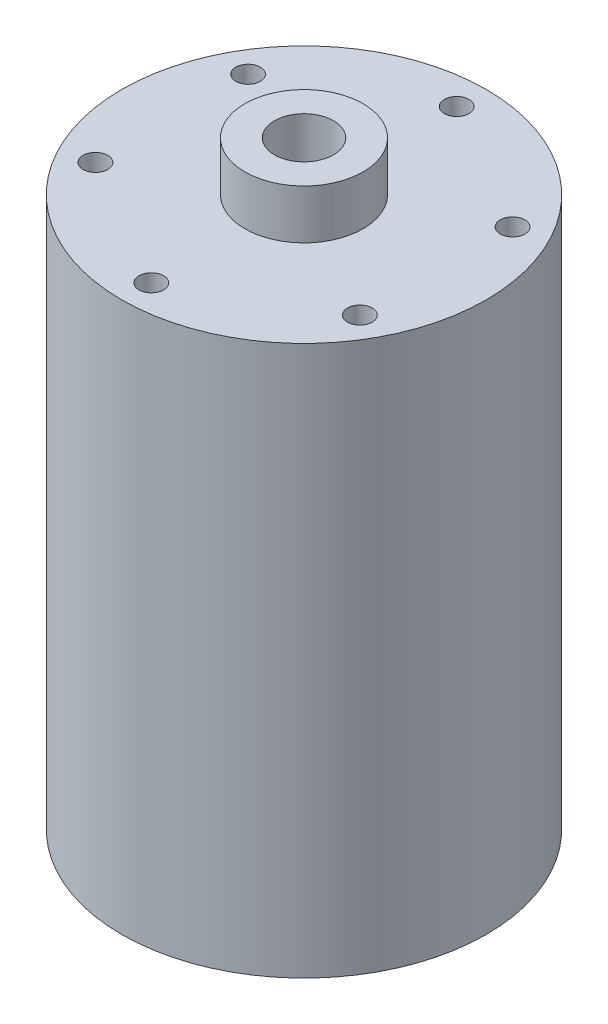
SolidWorks part; units mm, degrees
material "Plain Carbon Steel"
ref_plane "Front Plane" through (0, 0, 0) normal (0, 0, 1) x (1, 0, 0)
ref_plane "Top Plane" through (0, 0, 0) normal (0, 1, 0) x (1, 0, 0)
ref_plane "Right Plane" through (0, 0, 0) normal (1, 0, 0) x (0, 0, -1)
sketch "Sketch1" plane through (0, 0, 0) normal (0, 1, 0) x (1, 0, 0)
  circle A0 centre (0, 0) radius 18.5
  dimension "D1" = 37
extrude "Boss-Extrude1" add sketch "Sketch1" along normal blind 55.8
sketch "Sketch2" plane through (0, 55.8, 0) normal (0, 1, 0) x (1, 0, 0)
  circle A0 centre (0, 0) radius 6
  dimension "D1" = 12
extrude "Boss-Extrude2" add sketch "Sketch2" along normal blind 5
sketch "Sketch3" plane through (0, 55.8, 0) normal (0, 1, 0) x (1, 0, 0)
  circle A0 centre (0, 0) radius 15.5 construction
  dimension "D1" = 31
hole_wizard "M3x0.5 Tapped Hole1" positions "Sketch6" profile "Sketch7" tap size "M3x0.5" standard "ANSI Metric"
sketch "Sketch6" plane through (0, 55.8, 0) normal (0, 1, 0) x (1, 0, 0)
  point P0 (0, 15.5)
  point P10 (13.4234, 7.75)
  point P11 (13.4234, -7.75)
  point P12 (0, -15.5)
  point P13 (-13.4234, -7.75)
  point P14 (-13.4234, 7.75)
  point P16 (0, 0)
  dimension "D1" = 15.5
  dimension "D2" = 6
sketch "Sketch7" plane through (0, 55.8, -15.5) normal (1, 0, 0) x (0, 0, 1)
  line L0 (0, 0) -> (0, 11.4211)
  line L1 (0, 11.4211) -> (1.25, 10.67)
  line L2 (1.25, 10.67) -> (1.25, 0)
  line L5 (1.25, 0) -> (0, 0)
  line L10 (0, 11.4211) -> (-1.25, 10.67) construction
  line L11 (0, -6.35) -> (0, 107.95) construction
  dimension "Tap Drill Dia." = 2.5
  dimension "Tap Drill Depth" = 10.67
  dimension "Drill Angle" = 118
cosmetic thread "Hole Thread1" parameters "D1"=6, "D2"=3
cosmetic thread "Hole Thread2" parameters "D1"=6, "D2"=3
cosmetic thread "Hole Thread3" parameters "D1"=6, "D2"=3
cosmetic thread "Hole Thread4" parameters "D1"=6, "D2"=3
cosmetic thread "Hole Thread5" parameters "D1"=6, "D2"=3
cosmetic thread "Hole Thread6" parameters "D1"=6, "D2"=3
sketch "Sketch8" plane through (0, 60.8, 0) normal (0, 1, 0) x (1, 0, 0)
  circle A0 centre (0, 0) radius 3
  dimension "D1" = 6
extrude "Cut-Extrude1" cut sketch "Sketch8" against normal blind 5
